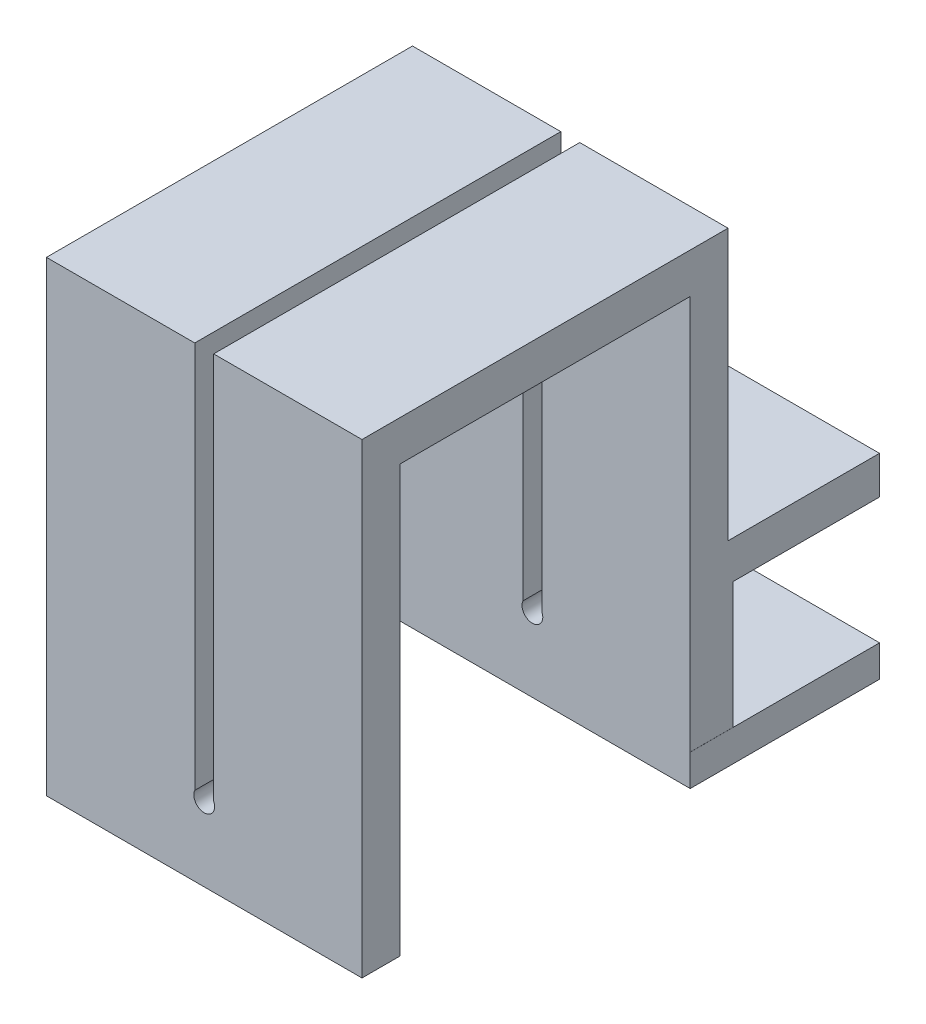
SolidWorks part; units mm, degrees
ref_plane "Спереди" through (0, 0, 0) normal (0, 0, 1) x (1, 0, 0)
ref_plane "Сверху" through (0, 0, 0) normal (0, 1, 0) x (1, 0, 0)
ref_plane "Справа" through (0, 0, 0) normal (1, 0, 0) x (0, 0, -1)
sketch "Эскиз1" plane through (0, 0, 0) normal (0, 0, 1) x (1, 0, 0)
  line L0 (25, 0) -> (25, 30) construction
  line L1 (0, 0) -> (8.5, 0)
  line L2 (0, 0) -> (0, 10)
  line L3 (20, 30) -> (30, 30)
  line L4 (50, 0) -> (50, 10)
  line L5 (8.5, 0) -> (11.5, 0)
  line L17 (38.5, 0) -> (41.5, 0)
  line L29 (11.5, 0) -> (38.5, 0)
  line L30 (41.5, 0) -> (50, 0)
  line L31 (25, 22.5) -> (25, 7.5) construction
  line L32 (28, 22.5) -> (28, 7.5)
  line L33 (22, 22.5) -> (22, 7.5)
  line L34 (0, 10) -> (0, 30)
  line L35 (0, 30) -> (20, 30)
  line L36 (50, 10) -> (50, 30)
  line L37 (50, 30) -> (30, 30)
  arc A0 (28, 22.5) -> (22, 22.5) centre (25, 22.5) ccw
  arc A1 (22, 7.5) -> (28, 7.5) centre (25, 7.5) ccw
  point P39 (25, 15)
  dimension "D1" = 50
  dimension "D7" = 6
  dimension "D8" = 15
  dimension "D10" = 30
  dimension "D11" = 15
extrude "Бобышка-Вытянуть1" add sketch "Эскиз1" along normal blind 6
sketch "Эскиз2" plane through (0, 0, 6) normal (0, 0, 1) x (1, 0, 0)
  line L1 (0, 0) -> (50.0107, 0)
  line L2 (0, 0) -> (0, -5)
  line L3 (0, -5) -> (50.0107, -5)
  line L4 (50.0107, 0) -> (50.0107, -5)
  dimension "D1" = 5
extrude "Бобышка-Вытянуть2" add sketch "Эскиз2" against normal blind 30
sketch "Эскиз4" plane through (0, 0, 0) normal (0, 1, 0) x (1, 0, 0)
  line L0 (0, 24) -> (0, 0) construction
  line L1 (50.0107, 24) -> (50.0107, -6) construction
  line L2 (50.0107, 24) -> (0, 24) construction
  circle A0 centre (25, 14) radius 1.75
  dimension "D1" = 3.5
  dimension "D2" = 25
  dimension "D3" = 25.0107
  dimension "D4" = 10
extrude "Вырез-Вытянуть1" cut sketch "Эскиз4" against normal blind 30
sketch "Эскиз6" plane through (0, 0, 0) normal (0, 1, 0) x (1, 0, 0)
  line L0 (30, 11) -> (20, 11)
  line L1 (30, 11) -> (30, 17)
  line L2 (30, 17) -> (20, 17)
  line L3 (20, 11) -> (20, 17)
  circle A0 centre (25, 14) radius 1.75
  circle A1 centre (25, 14) radius 1.75 construction
  dimension "D3" = 3.5
  dimension "D6" = 0
  dimension "D7" = 0
  dimension "D1" = 6
  dimension "D2" = 10
  dimension "D4" = 3
  dimension "D5" = 5
extrude "Бобышка-Вытянуть4" add sketch "Эскиз6" along normal blind 1.5
sketch "Эскиз7" plane through (0, 0, 0) normal (-1, 0, 0) x (0, 0, 1)
  line L0 (58, -5) -> (58, 68.8953)
  line L1 (6, -5) -> (0, -5)
  line L2 (6, -5) -> (6, 62.5241)
  line L4 (0, -5) -> (0, 62.5241)
  line L7 (6, 62.5241) -> (52, 62.5241)
  line L11 (58, -5) -> (52, -5)
  line L12 (52, 62.5241) -> (52, -5)
  line L13 (58, 68.8953) -> (0, 68.8953)
  line L14 (0, 68.8953) -> (0, 62.5241)
  dimension "D1" = 6
  dimension "D2" = 6
  dimension "D3" = 6.3712
  dimension "D4" = 46
sketch "Эскиз8" plane through (0, 0, 0) normal (0, 0, -1) x (-1, 0, 0)
  line L0 (-26.5, 112.5) -> (-23.5, 112.5)
  line L9 (-25, 19.9019) -> (-25, 6.8218) construction
  line L10 (-23.5, 112.5) -> (-23.5, 7.5)
  line L11 (-26.5, 112.5) -> (-26.5, 7.5)
  line L12 (-26.5, 7.5) -> (-23.5, 7.5) construction
  arc A2 (-26.5, 7.5) -> (-23.5, 7.5) centre (-25, 6.8218) ccw
  arc A3 (-22, 22.5) -> (-28, 22.5) centre (-25, 22.5) ccw construction
  point P12 (-25, 15)
  dimension "D1" = 105
  dimension "D3" = 0
  dimension "D2" = 3
extrude "Бобышка-Вытянуть6" add sketch "Эскиз7" against normal up to surface (50 mm away) up to face at (50, 15, 3)
extrude "Вырез-Вытянуть2" cut sketch "Эскиз8" against normal up to surface (58 mm away) contours L11 A2 L10 L0 up to face at (25, 31.9477, 58)
sketch "Эскиз15" plane through (0, 0, 0) normal (0, 1, 0) x (1, 0, 0)
  line L1 (50, 0) -> (48.9759, 0)
  line L2 (50, 0) -> (50, 0.7688)
  line L3 (50, 0.7688) -> (48.9759, 0.7688)
  line L4 (48.9759, 0) -> (48.9759, 0.7688)
extrude "Бобышка-Вытянуть10" add sketch "Эскиз15" along normal blind 20
sketch "Эскиз16" plane through (0, 20, 0) normal (0, 1, 0) x (1, 0, 0)
  line L0 (0, -58) -> (0, 0) construction
  line L1 (50, 0) -> (28.5, 0)
  line L2 (50, 0) -> (50, 24)
  line L3 (50, 24) -> (0, 24)
  line L4 (0, 0) -> (0, 24)
  line L5 (50.0107, 24) -> (0, 24) construction
  line L10 (21.5, 0) -> (21.5, 4)
  line L11 (21.5, 4) -> (28.5, 4)
  line L12 (28.5, 4) -> (28.5, 0)
  line L13 (21.5, 0) -> (0, 0)
  dimension "D1" = 0
  dimension "D2" = 0
  dimension "D3" = 4
  dimension "D4" = 2
  dimension "D6" = 2
extrude "Бобышка-Вытянуть11" add sketch "Эскиз16" along normal blind 6 contours L4 L3 L2 L1 L12 L11 L10 L13
sketch "Эскиз17" plane through (0, 20, 0) normal (0, -1, 0) x (1, 0, 0)
  line L0 (30, -17) -> (20, -17)
  line L1 (30, -17) -> (30, -11)
  line L2 (30, -11) -> (20, -11)
  line L3 (20, -17) -> (20, -11)
  circle A0 centre (25, -14) radius 1.75
  circle A1 centre (25, -14) radius 1.75 construction
  dimension "D3" = 3.5
  dimension "D6" = 0
  dimension "D7" = 0
  dimension "D1" = 6
  dimension "D2" = 10
  dimension "D4" = 3
  dimension "D5" = 5
extrude "Бобышка-Вытянуть12" add sketch "Эскиз17" along normal blind 1.5
sketch "Эскиз18" plane through (0, 18.5, 0) normal (0, -1, 0) x (1, 0, 0)
  circle A0 centre (25, -14) radius 1.75
extrude "Вырез-Вытянуть3" cut sketch "Эскиз18" against normal blind 100
